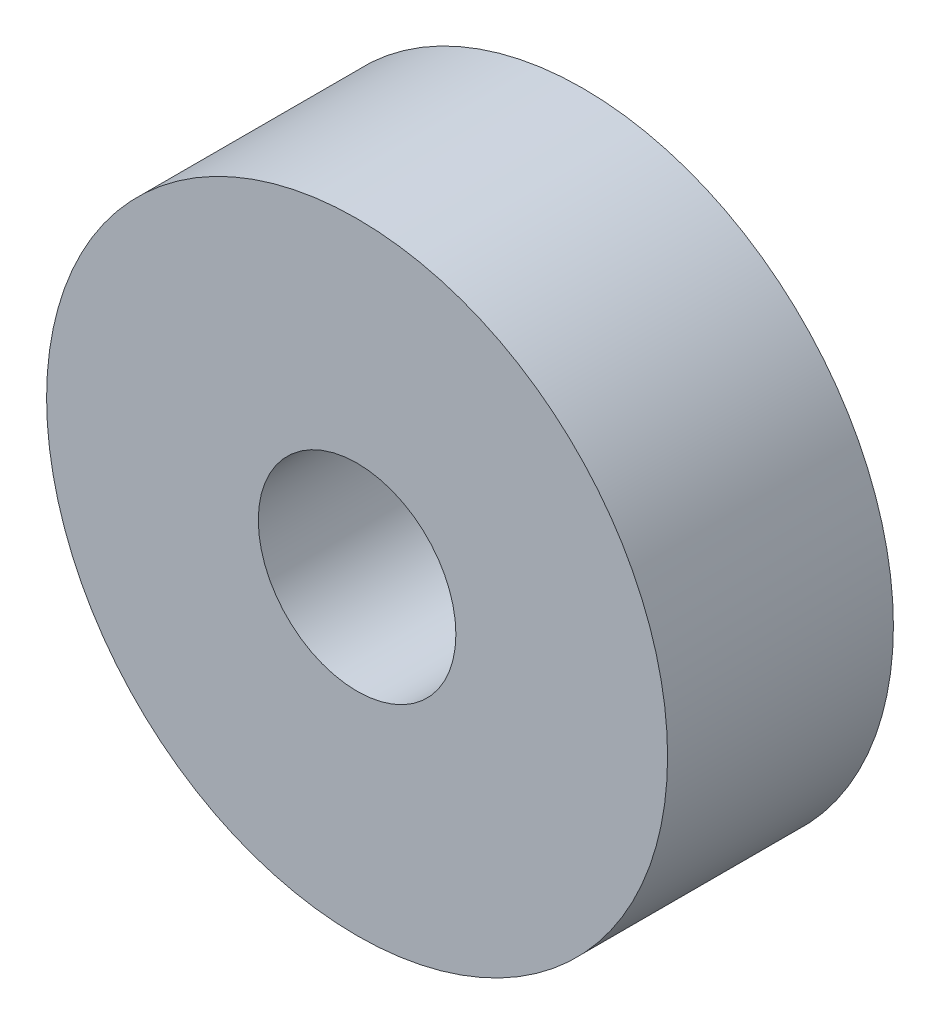
SolidWorks part; units mm, degrees
ref_plane "Front Plane" through (0, 0, 0) normal (0, 0, 1) x (1, 0, 0)
ref_plane "Top Plane" through (0, 0, 0) normal (0, 1, 0) x (1, 0, 0)
ref_plane "Right Plane" through (0, 0, 0) normal (1, 0, 0) x (0, 0, -1)
sketch "Sketch1" plane through (0, 0, 0) normal (0, 0, 1) x (1, 0, 0)
  circle A0 centre (31.9156, 315) radius 11
  circle A1 centre (31.9156, 315) radius 3.5
  dimension "D1" = 7
  dimension "D2" = 22
extrude "Boss-Extrude1" add sketch "Sketch1" along normal blind 8
